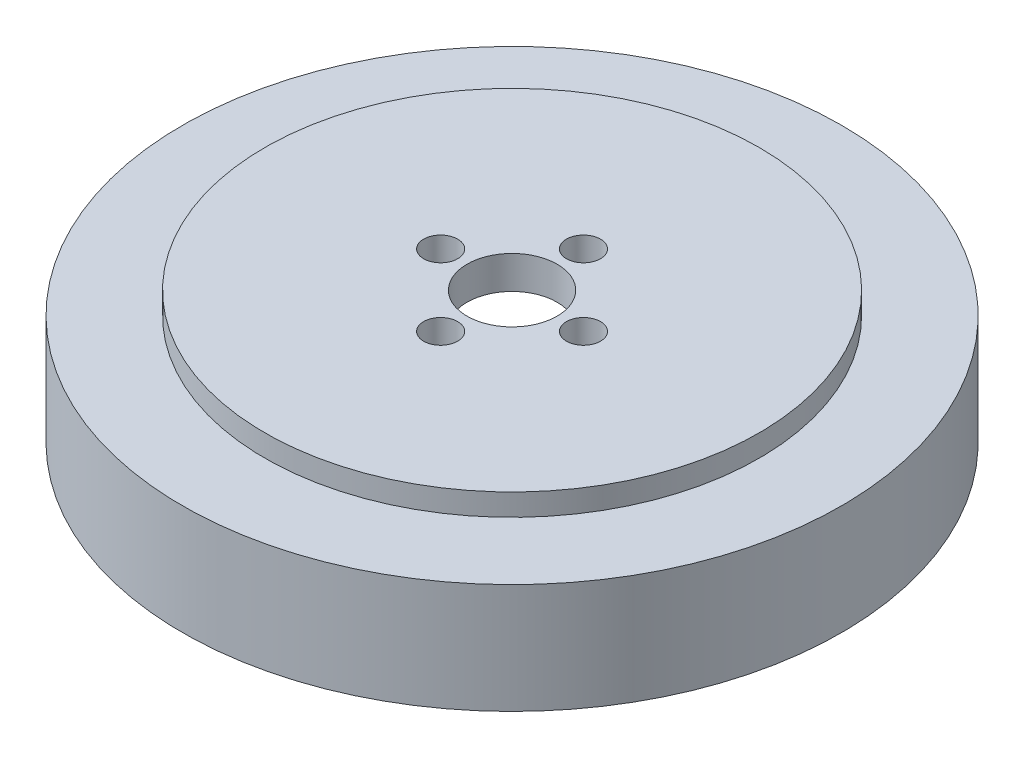
SolidWorks part; units mm, degrees
material "6061 Alloy"
ref_plane "前视基准面" through (0, 0, 0) normal (0, 0, 1) x (1, 0, 0)
ref_plane "上视基准面" through (0, 0, 0) normal (0, 1, 0) x (1, 0, 0)
ref_plane "右视基准面" through (0, 0, 0) normal (1, 0, 0) x (0, 0, -1)
sketch "草图1" plane through (0, 0, 0) normal (0, 0, 1) x (1, 0, 0)
  line L0 (4.1, 0) -> (4.1, 3)
  line L1 (4.1, 3) -> (22.5, 3)
  line L2 (22.5, 3) -> (22.5, -10)
  line L3 (22.5, -10) -> (21, -10)
  line L4 (21, -10) -> (21, 0)
  line L5 (21, 0) -> (4.1, 0)
  line L7 (0, 0) -> (0, 6.7525) construction
  dimension "D1" = 3
  dimension "D2" = 42
  dimension "D3" = 1.5
  dimension "D4" = 13
  dimension "D5" = 8.2
revolve "旋转1" add sketch "草图1" angle 360 about L7
sketch "草图2" plane through (0, 0, 0) normal (0, 0, 1) x (1, 0, 0)
  line L0 (22.5, -10) -> (22.5, 3) construction
  line L1 (22.5, 1) -> (30, 1)
  line L2 (22.5, 1) -> (22.5, -9)
  line L3 (22.5, -9) -> (30, -9)
  line L4 (30, 1) -> (30, -9)
  line L5 (0, 0) -> (0, 16.7786) construction
  line L6 (22.5, 3) -> (-22.5, 3) construction
  dimension "D1" = 30
  dimension "D2" = 10
  dimension "D3" = 2
revolve "旋转2" add sketch "草图2" angle 360 about L5
sketch "草图3" plane through (0, 0, 0) normal (0, -1, 0) x (1, 0, 0)
  line L0 (0, 0) -> (0, -14.0749) construction
  circle A0 centre (6.5, 0) radius 1.55
  circle A1 centre (-6.5, 0) radius 1.55
  circle A2 centre (0, 6.5) radius 1.55
  circle A3 centre (6.5, 0) radius 1.55 [skipped]
  circle A4 centre (0, -6.5) radius 1.55
  point P16 (0, 0)
  dimension "D1" = 13
  dimension "D2" = 3.1
  dimension "D3" = 4
extrude "切除-拉伸1" cut sketch "草图3" against normal blind 10
